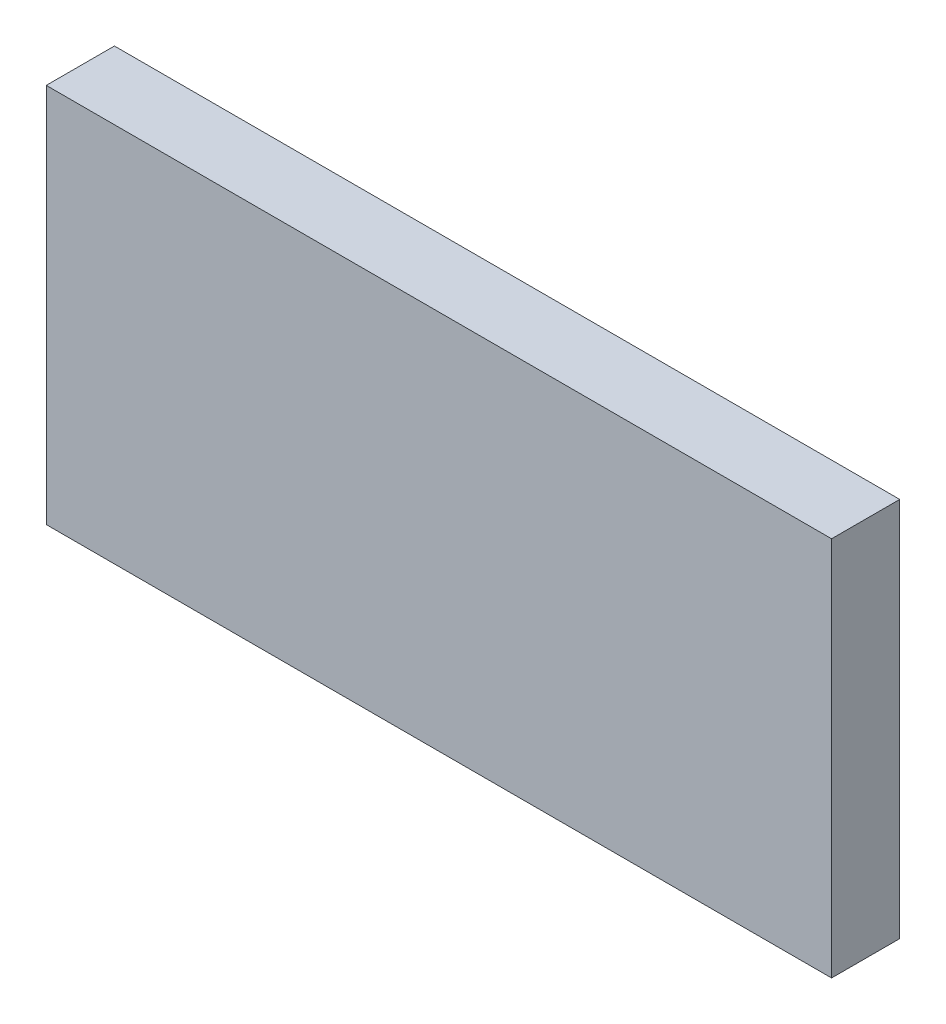
SolidWorks part; units mm, degrees
ref_plane "Front Plane" through (0, 0, 0) normal (0, 0, 1) x (1, 0, 0)
ref_plane "Top Plane" through (0, 0, 0) normal (0, 1, 0) x (1, 0, 0)
ref_plane "Right Plane" through (0, 0, 0) normal (1, 0, 0) x (0, 0, -1)
sketch "Sketch1" plane through (0, 0, 0) normal (0, 0, 1) x (1, 0, 0)
  line L1 (-28.1748, 19.6711) -> (20.5932, 19.6711)
  line L2 (-28.1748, 19.6711) -> (-28.1748, -3.9509)
  line L3 (-28.1748, -3.9509) -> (20.5932, -3.9509)
  line L4 (20.5932, 19.6711) -> (20.5932, -3.9509)
  dimension "D1" = 48.768
  dimension "D2" = 23.622
extrude "Boss-Extrude1" add sketch "Sketch1" along normal blind 4.2333
